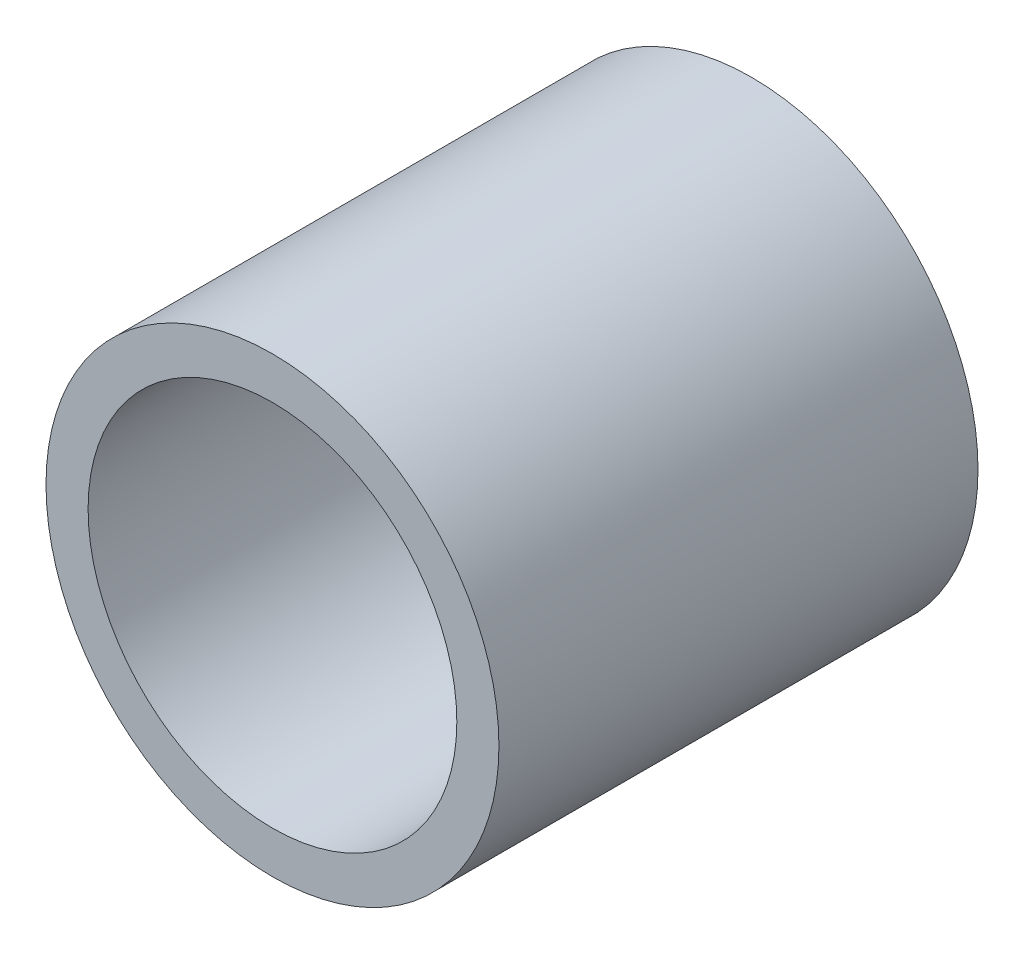
SolidWorks part; units mm, degrees
ref_plane "前视基准面" through (0, 0, 0) normal (0, 0, 1) x (1, 0, 0)
ref_plane "上视基准面" through (0, 0, 0) normal (0, 1, 0) x (1, 0, 0)
ref_plane "右视基准面" through (0, 0, 0) normal (1, 0, 0) x (0, 0, -1)
sketch "草图1" plane through (0, 0, 0) normal (0, 0, 1) x (1, 0, 0)
  circle A1 centre (0, 0) radius 12.6
  circle A2 centre (9, 0) radius 1.65
  circle A3 centre (-9, 0) radius 1.65
  circle A4 centre (0, 0) radius 15.6
  circle A5 centre (0, 0) radius 6.3
extrude "凸台-拉伸1" add sketch "草图1" along normal blind 3 contours A4 A1 | A1 A5 A3 A2
sketch "草图2" plane through (0, 0, 3) normal (0, 0, 1) x (1, 0, 0)
  circle A0 centre (0, 0) radius 12.7
  circle A1 centre (0, 0) radius 15.6
extrude "凸台-拉伸2" add sketch "草图2" along normal blind 30
